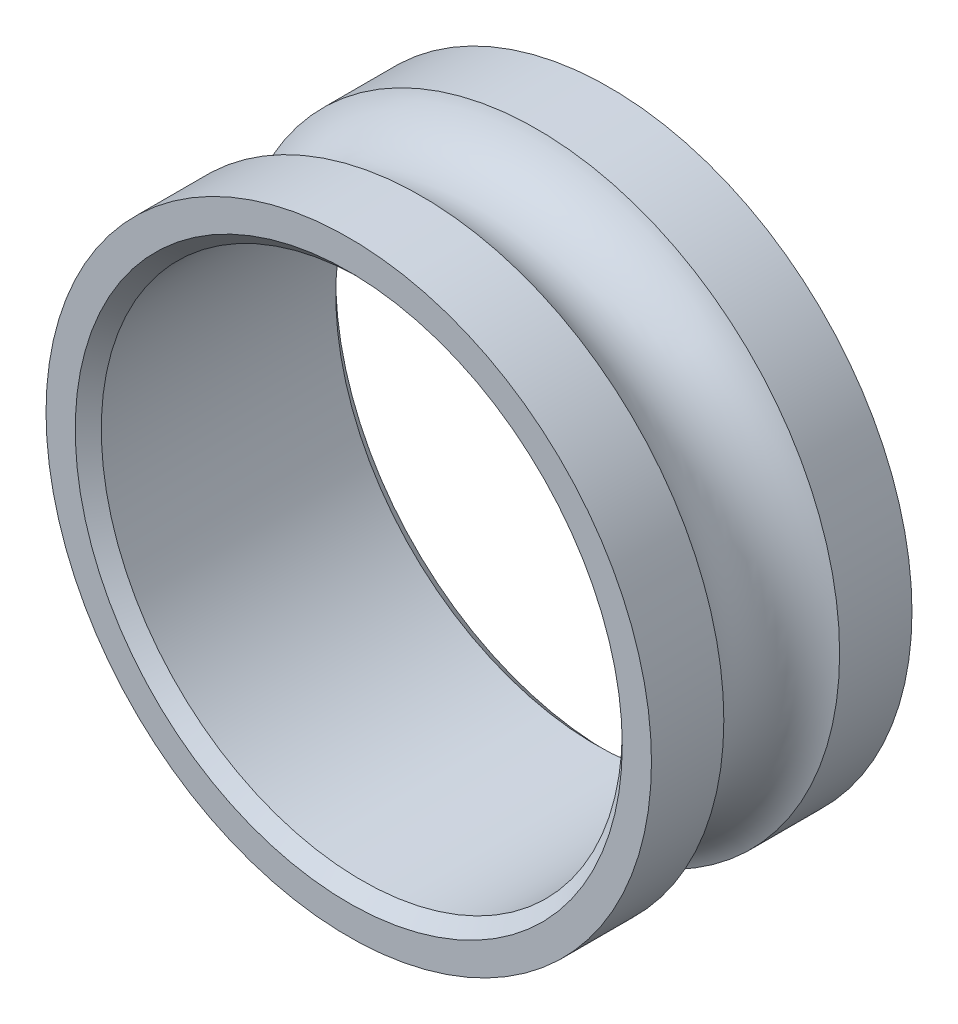
SolidWorks part; units mm, degrees
ref_plane "Front Plane" through (0, 0, 0) normal (0, 0, 1) x (1, 0, 0)
ref_plane "Top Plane" through (0, 0, 0) normal (0, 1, 0) x (1, 0, 0)
ref_plane "Right Plane" through (0, 0, 0) normal (1, 0, 0) x (0, 0, -1)
sketch "Sketch1" plane through (0, 0, 0) normal (0, 1, 0) x (1, 0, 0)
  line L0 (3.6896, -1.5875) -> (3.6896, -0.7056)
  line L1 (3.6896, 0.7056) -> (3.6896, 1.5875)
  line L2 (3.6896, 1.5875) -> (3.3337, 1.5875)
  line L3 (3.3337, 1.5875) -> (3.175, 1.4288)
  line L4 (3.175, 1.4288) -> (3.175, -1.4287)
  line L5 (3.175, -1.4287) -> (3.3338, -1.5875)
  line L6 (3.3338, -1.5875) -> (3.6896, -1.5875)
  line L7 (0, 1.5875) -> (0, -1.5875) construction
  arc A0 (3.6896, -0.7056) -> (3.6896, 0.7056) centre (3.9687, 0) cw
revolve "Revolve1" add sketch "Sketch1" angle 360 about L7
